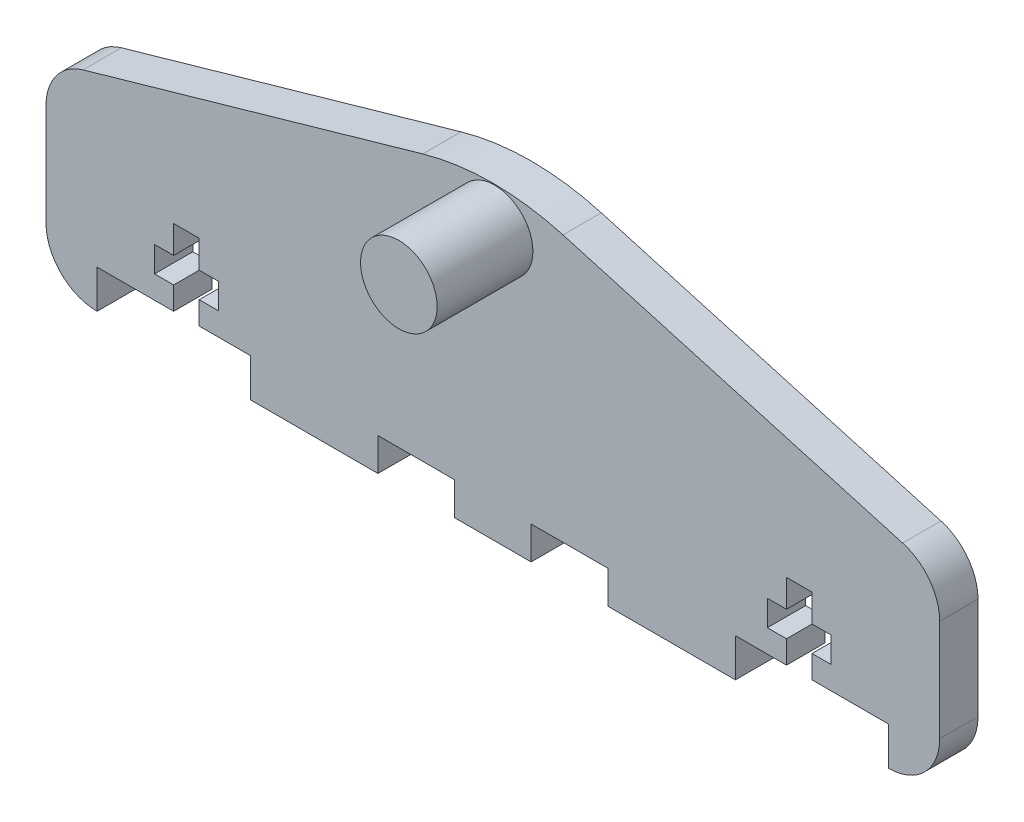
SolidWorks part; units mm, degrees
ref_plane "Plan de face" through (0, 0, 0) normal (0, 0, 1) x (1, 0, 0)
ref_plane "Plan de dessus" through (0, 0, 0) normal (0, 1, 0) x (1, 0, 0)
ref_plane "Plan de droite" through (0, 0, 0) normal (1, 0, 0) x (0, 0, -1)
sketch "Esquisse1" plane through (0, 0, 0) normal (0, 0, 1) x (1, 0, 0)
  line L0 (-160.4944, 41.6445) -> (-27.4721, 79.6508)
  line L1 (-155, -37.5) -> (155, -37.5)
  line L2 (-175, -17.5) -> (-175, 22.414)
  line L3 (-175, 37.5) -> (175, 37.5) construction
  line L4 (175, -17.5) -> (175, 22.414)
  line L5 (-175, -37.5) -> (175, 37.5) construction
  line L6 (-175, 37.5) -> (175, -37.5) construction
  line L7 (27.4721, 79.6508) -> (160.4944, 41.6445)
  line L8 (0, 83.4984) -> (0, -16.5016) construction
  line L9 (-175, -17.5) -> (175, -17.5) construction
  line L10 (-175, 22.414) -> (175, 22.414) construction
  arc A0 (27.4721, 79.6508) -> (-27.4721, 79.6508) centre (0, -16.5016) ccw
  circle A1 centre (0, 68.1651) radius 5
  arc A2 (175, 22.414) -> (160.4944, 41.6445) centre (155, 22.414) ccw
  arc A3 (155, -37.5) -> (175, -17.5) centre (155, -17.5) ccw
  arc A4 (-155, -37.5) -> (-175, -17.5) centre (-155, -17.5) cw
  arc A5 (-175, 22.414) -> (-160.4944, 41.6445) centre (-155, 22.414) cw
  point P0 (0, 0)
  dimension "D3" = 100
  dimension "D4" = 10
  dimension "D5" = 20
  dimension "D1" = 350
  dimension "D2" = 75
  dimension "D6" = 15.3333
extrude "Boss.-Extru.1" add sketch "Esquisse1" along normal blind 15
sketch "Esquisse2" plane through (0, 0, 15) normal (0, 0, 1) x (1, 0, 0)
  line L0 (-175, -17.5) -> (175, -17.5) construction
  line L1 (175, -17.5) -> (175, 22.414) construction
  line L2 (115, -60) -> (125, -60)
  line L3 (115, -60) -> (115, -37.5)
  line L4 (115, 7.276) -> (125, 7.276)
  line L5 (125, -60) -> (125, -37.5)
  line L6 (115, -60) -> (125, 7.276) construction
  line L7 (115, 7.276) -> (125, -60) construction
  line L8 (0, 0) -> (0, -37.5) construction
  line L9 (-155, -37.5) -> (155, -37.5) construction
  line L10 (120, 7.276) -> (120, -60) construction
  line L11 (107.5, -13.5497) -> (115, -13.5497)
  line L12 (107.5, -13.5497) -> (107.5, -3.5497)
  line L13 (107.5, -3.5497) -> (115, -3.5497)
  line L14 (132.5, -13.5497) -> (132.5, -3.5497)
  line L15 (107.5, -13.5497) -> (132.5, -3.5497) construction
  line L16 (107.5, -3.5497) -> (132.5, -13.5497) construction
  line L17 (135, -22.5) -> (135, -37.5)
  line L18 (135, -22.5) -> (125, -22.5)
  line L19 (135, -37.5) -> (125, -37.5)
  line L20 (95, -22.5) -> (95, -37.5)
  line L21 (95, -22.5) -> (95, -37.5)
  line L22 (-115, -60) -> (-125, -60)
  line L23 (-125, -60) -> (-125, -37.5)
  line L24 (45, -24.6183) -> (45, -37.5)
  line L25 (45, -24.6183) -> (45, -37.5)
  line L26 (45, -24.6183) -> (15, -24.6183)
  line L27 (45, -37.5) -> (15, -37.5)
  line L28 (15, -24.6183) -> (15, -37.5)
  line L29 (-115, 7.276) -> (-125, 7.276)
  line L30 (-107.5, -13.5497) -> (-107.5, -3.5497)
  line L31 (-132.5, -13.5497) -> (-132.5, -3.5497)
  line L32 (-107.5, -3.5497) -> (-115, -3.5497)
  line L33 (-107.5, -13.5497) -> (-115, -13.5497)
  line L34 (-115, -60) -> (-115, -37.5)
  line L35 (-135, -37.5) -> (-125, -37.5)
  line L36 (-135, -22.5) -> (-125, -22.5)
  line L37 (-95, -22.5) -> (-95, -37.5)
  line L38 (-45, -24.6183) -> (-45, -37.5)
  line L39 (-45, -37.5) -> (-15, -37.5)
  line L40 (-15, -24.6183) -> (-15, -37.5)
  line L41 (-45, -24.6183) -> (-15, -24.6183)
  line L42 (-135, -22.5) -> (-135, -37.5)
  line L46 (45, -37.5) -> (45, -22.5) construction
  line L47 (95, -37.5) -> (95, -22.5) construction
  line L48 (-155, -37.5) -> (155, -37.5) construction
  line L49 (115, -22.5) -> (115, -13.5497)
  line L50 (125, -22.5) -> (125, -13.5497)
  line L51 (115, -22.5) -> (95, -22.5)
  line L52 (115, -3.5497) -> (115, 7.276)
  line L53 (125, -3.5497) -> (132.5, -3.5497)
  line L54 (125, -3.5497) -> (125, 7.276)
  line L55 (125, -13.5497) -> (132.5, -13.5497)
  line L56 (-125, -22.5) -> (-125, -13.5497)
  line L57 (115, -37.5) -> (95, -37.5)
  line L58 (-115, -22.5) -> (-115, -13.5497)
  line L59 (-115, -22.5) -> (-95, -22.5)
  line L60 (-125, -13.5497) -> (-132.5, -13.5497)
  line L61 (-125, -3.5497) -> (-125, 7.276)
  line L62 (-115, -3.5497) -> (-115, 7.276)
  line L63 (-125, -3.5497) -> (-132.5, -3.5497)
  line L64 (-115, -37.5) -> (-95, -37.5)
  point P4 (120, -26.362)
  point P16 (120, -8.5497)
  line M24 (-155, -37.5) -> (155, -37.5)
  dimension "D1" = 50
  dimension "D2" = 10
  dimension "D3" = 25
  dimension "D4" = 10
  dimension "D5" = 15
  dimension "D6" = 40
  dimension "D8" = 30
extrude "Enlèv. mat.-Extru.1" cut sketch "Esquisse2" against normal blind 15 contours L50 L55 L14 L53 L54 L4 L52 L13 L12 L11 L49 L51 L20 L17 L18 M24 | L26 L28 L24 M24 | L41 L38 L40 M24 | L61 L63 L31 L60 L56 L36 L42 L37 L59 L58 L33 L30 L32 L62 L29 M24
sketch "Esquisse3" plane through (0, 0, 0) normal (0, 0, -1) x (-1, 0, 0)
  line L0 (135, -22.5) -> (135, -37.5)
  line L1 (135, -22.5) -> (155, -22.5)
  line L2 (135, -37.5) -> (155, -37.5)
  line L3 (155, -22.5) -> (155, -37.5)
  line L4 (155, -37.5) -> (155, -22.5) construction
  line L5 (0, -37.5) -> (0, 30.1236) construction
  line L6 (15, -37.5) -> (-15, -37.5) construction
  line L7 (-155, -22.5) -> (-155, -37.5)
  line L8 (-135, -37.5) -> (-155, -37.5)
  line L9 (-135, -22.5) -> (-135, -37.5)
  line L10 (-135, -22.5) -> (-155, -22.5)
extrude "Enlèv. mat.-Extru.2" cut sketch "Esquisse3" against normal blind 15
sketch "Esquisse5" plane through (0, 0, 15) normal (0, 0, 1) x (1, 0, 0)
  circle A0 centre (0.6859, 68.1651) radius 15
  dimension "D1" = 30
extrude "Boss.-Extru.2" add sketch "Esquisse5" along normal blind 37.5
